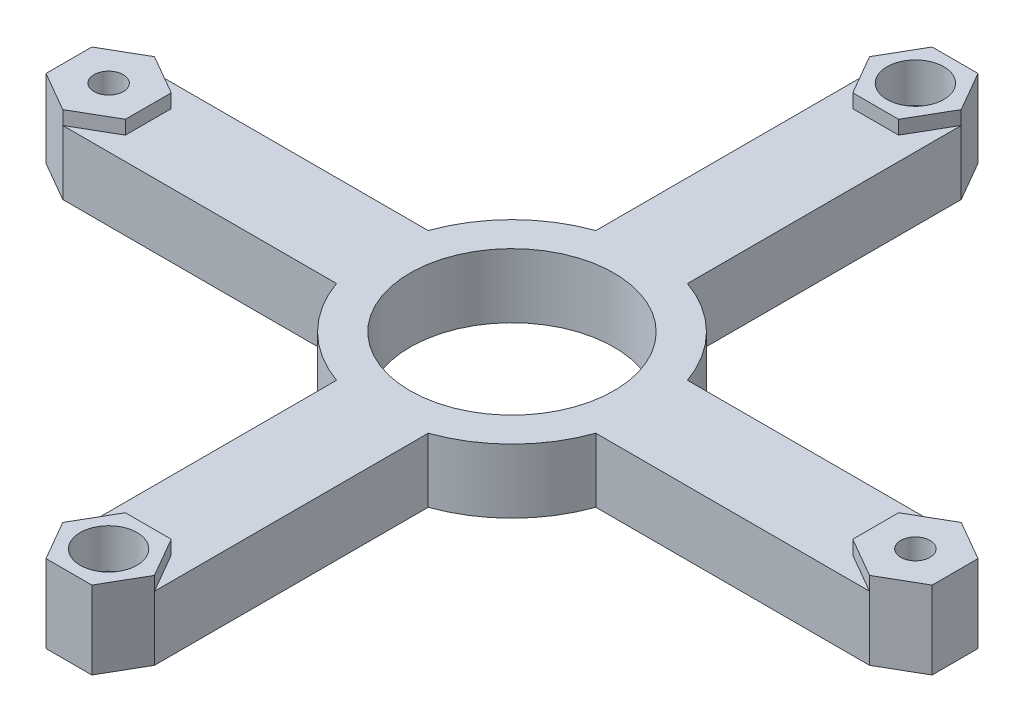
SolidWorks part; units mm, degrees
ref_plane "Front Plane" through (0, 0, 0) normal (0, 0, 1) x (1, 0, 0)
ref_plane "Top Plane" through (0, 0, 0) normal (0, 1, 0) x (1, 0, 0)
ref_plane "Right Plane" through (0, 0, 0) normal (1, 0, 0) x (0, 0, -1)
sketch "Sketch1" plane through (0, 0, 0) normal (0, 1, 0) x (1, 0, 0)
  line L0 (0, 0) -> (0, 2984.5753) construction
  line L1 (0, 0) -> (2984.5753, 0) construction
  line L7 (44, 5) -> (48.3301, 2.5)
  line L8 (48.3301, 2.5) -> (48.3301, -2.5)
  line L13 (48.3301, -2.5) -> (44, -5)
  line L14 (5, -44) -> (2.5, -48.3301)
  line L15 (14.1421, 5) -> (44, 5)
  line L16 (2.5, -48.3301) -> (-2.5, -48.3301)
  line L17 (-2.5, -48.3301) -> (-5, -44)
  line L18 (14.1421, -5) -> (44, -5)
  line L19 (-5, -14.1421) -> (-5, -44)
  line L20 (-44, -5) -> (-48.3301, -2.5)
  line L21 (-48.3301, -2.5) -> (-48.3301, 2.5)
  line L22 (-48.3301, 2.5) -> (-44, 5)
  line L23 (-5, 44) -> (-2.5, 48.3301)
  line L24 (-2.5, 48.3301) -> (2.5, 48.3301)
  line L25 (2.5, 48.3301) -> (5, 44)
  line L26 (5, -14.1421) -> (5, -44)
  line L27 (-14.1421, 5) -> (-44, 5)
  line L28 (-44, -5) -> (-14.1421, -5)
  line L29 (-5, 44) -> (-5, 14.1421)
  line L30 (5, 44) -> (5, 14.1421)
  circle A0 centre (0, 0) radius 11.125
  arc A1 (5, -14.1421) -> (14.1421, -5) centre (0, 0) ccw
  circle A2 centre (44, 0) radius 1.6
  circle A3 centre (0, 44) radius 1.6
  circle A4 centre (-44, 0) radius 1.6
  circle A5 centre (0, -44) radius 1.6
  arc A6 (14.1421, 5) -> (5, 14.1421) centre (0, 0) ccw
  arc A7 (-5, 14.1421) -> (-14.1421, 5) centre (0, 0) ccw
  arc A8 (-14.1421, -5) -> (-5, -14.1421) centre (0, 0) ccw
  point P26 (48.3301, 0)
  point P49 (0, 0)
  dimension "D1" = 3.2
  dimension "D2" = 30
  dimension "D3" = 22.25
  dimension "D4" = 44
  dimension "D5" = 44
  dimension "D6" = 10
  dimension "D8" = 60
  dimension "D9" = 4
extrude "Boss-Extrude1" add sketch "Sketch1" along normal blind 7
sketch "Sketch3" plane through (0, 7, 0) normal (0, 1, 0) x (1, 0, 0)
  circle A0 centre (0, 44) radius 3.1
  circle A1 centre (0, 44) radius 1.6 construction
  circle A2 centre (0, -44) radius 3.1
  circle A3 centre (0, -44) radius 1.6 construction
  dimension "D1" = 6.2
  dimension "D2" = 6.2
extrude "Cut-Extrude1" cut sketch "Sketch3" against normal blind 2.8
sketch "Sketch2" plane through (0, 7, 0) normal (0, 1, 0) x (1, 0, 0)
  line L1 (-44, 5) -> (-48.3301, 2.5)
  line L2 (-48.3301, 2.5) -> (-48.3301, -2.5)
  line L3 (-48.3301, -2.5) -> (-44, -5)
  line L4 (-44, -5) -> (-39.6699, -2.5)
  line L5 (-39.6699, -2.5) -> (-39.6699, 2.5)
  line L6 (-39.6699, 2.5) -> (-44, 5)
  line L7 (48.3301, 2.5) -> (44, 5)
  line L8 (44, 5) -> (39.6699, 2.5)
  line L9 (39.6699, 2.5) -> (39.6699, -2.5)
  line L10 (39.6699, -2.5) -> (44, -5)
  line L11 (44, -5) -> (48.3301, -2.5)
  line L12 (48.3301, -2.5) -> (48.3301, 2.5)
  line L13 (2.5, 48.3301) -> (-2.5, 48.3301)
  line L14 (-2.5, 48.3301) -> (-5, 44)
  line L15 (-5, 44) -> (-2.5, 39.6699)
  line L16 (-2.5, 39.6699) -> (2.5, 39.6699)
  line L17 (2.5, 39.6699) -> (5, 44)
  line L18 (5, 44) -> (2.5, 48.3301)
  line L19 (-2.5, -48.3301) -> (2.5, -48.3301)
  line L20 (2.5, -48.3301) -> (5, -44)
  line L21 (5, -44) -> (2.5, -39.6699)
  line L22 (2.5, -39.6699) -> (-2.5, -39.6699)
  line L23 (-2.5, -39.6699) -> (-5, -44)
  line L24 (-5, -44) -> (-2.5, -48.3301)
  circle A0 centre (-44, 0) radius 4.3301 construction
  circle A1 centre (44, 0) radius 4.3301 construction
  circle A2 centre (44, 0) radius 1.6
  circle A3 centre (-44, 0) radius 1.6
  circle A4 centre (-44, 0) radius 1.6 construction
  circle A5 centre (44, 0) radius 1.6 construction
  circle A6 centre (0, 44) radius 4.3301 construction
  circle A7 centre (0, 44) radius 1.6 construction
  circle A8 centre (0, 44) radius 3.1
  circle A9 centre (0, 44) radius 3.1 construction
  circle A10 centre (0, -44) radius 4.3301 construction
  circle A11 centre (0, -44) radius 1.6 construction
  circle A12 centre (0, -44) radius 3.1
  circle A13 centre (0, -44) radius 3.1 construction
extrude "Boss-Extrude2" add sketch "Sketch2" along normal blind 1.5
